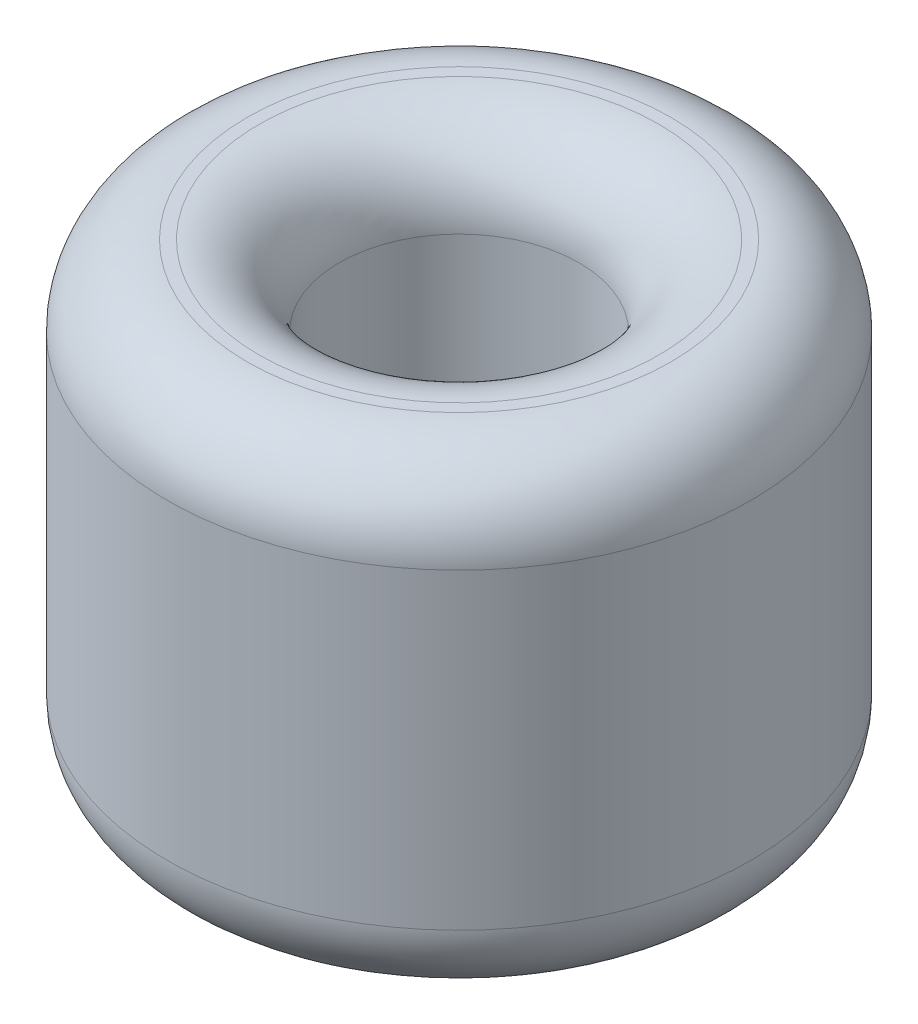
SolidWorks part; units mm, degrees
ref_plane "Front Plane" through (0, 0, 0) normal (0, 0, 1) x (1, 0, 0)
ref_plane "Top Plane" through (0, 0, 0) normal (0, 1, 0) x (1, 0, 0)
ref_plane "Right Plane" through (0, 0, 0) normal (1, 0, 0) x (0, 0, -1)
sketch "Sketch1" plane through (0, 0, 0) normal (0, 0, 1) x (1, 0, 0)
  line L0 (1.5, 4.9) -> (1.5, 1)
  line L1 (2.5, 0) -> (2.65, 0)
  line L2 (3.65, 1) -> (3.65, 4.9)
  line L3 (2.65, 5.9) -> (2.5, 5.9)
  line L4 (0, 5.9029) -> (0, -0.0029) construction
  arc A0 (2.5, 5.9) -> (1.5, 4.9) centre (2.5, 4.9) ccw
  arc A1 (1.5, 1) -> (2.5, 0) centre (2.5, 1) ccw
  arc A2 (2.65, 0) -> (3.65, 1) centre (2.65, 1) ccw
  arc A3 (3.65, 4.9) -> (2.65, 5.9) centre (2.65, 4.9) ccw
revolve "Revolve1" add sketch "Sketch1" angle 360 about L4
